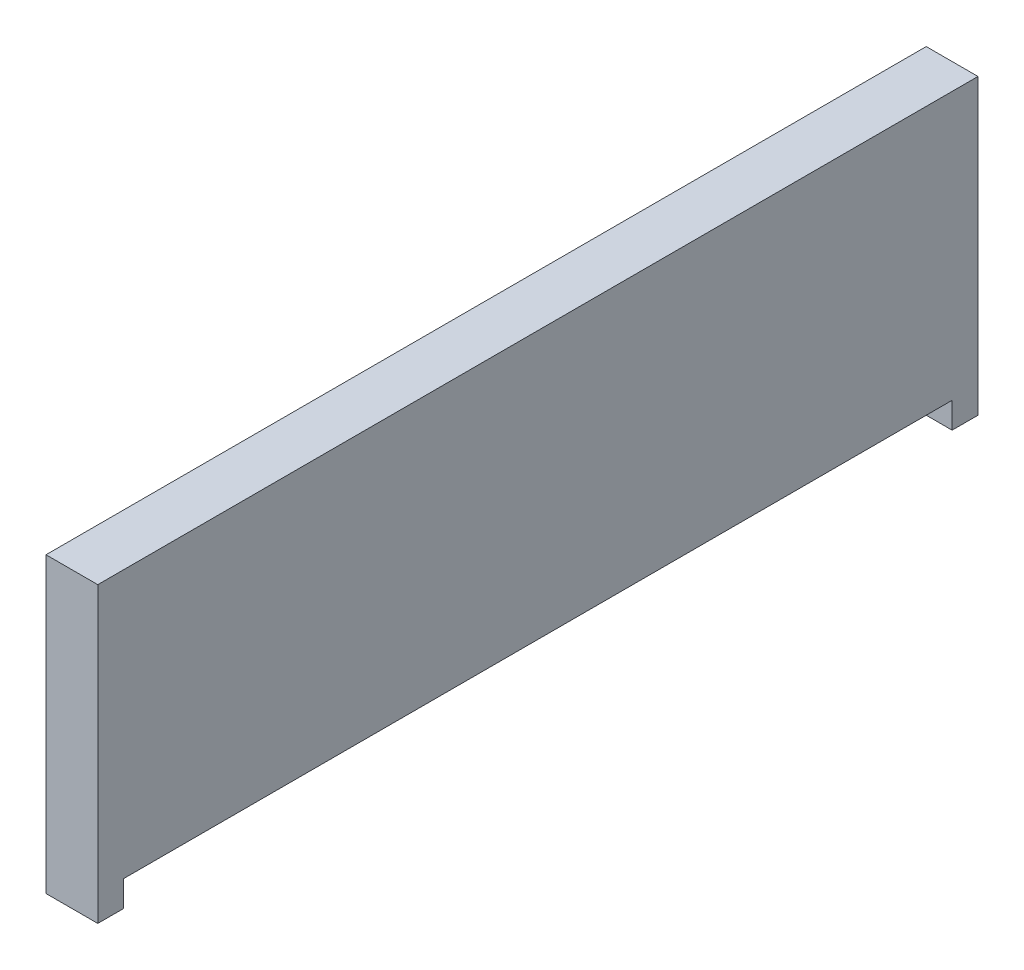
SolidWorks part; units mm, degrees
material "Сосна"
ref_plane "Спереди" through (0, 0, 0) normal (0, 0, 1) x (1, 0, 0)
ref_plane "Сверху" through (0, 0, 0) normal (0, 1, 0) x (1, 0, 0)
ref_plane "Справа" through (0, 0, 0) normal (1, 0, 0) x (0, 0, -1)
sketch "Эскиз1" plane through (0, 0, 0) normal (0, 0, 1) x (1, 0, 0)
  line L0 (0, 0) -> (15, 0)
  line L1 (15, 15) -> (30, 15)
  line L2 (15, 0) -> (15, 15)
  line L3 (30, 15) -> (30, 170)
  line L4 (30, 170) -> (0, 170)
  line L7 (0, 170) -> (0, 0)
  dimension "D1" = 155
  dimension "D2" = 30
  dimension "D3" = 15
  dimension "D4" = 15
extrude "Бобышка-Вытянуть1" add sketch "Эскиз1" along normal blind 510
sketch "Эскиз2" plane through (0, 0, 0) normal (0, 0, -1) x (-1, 0, 0)
  line L1 (-30, 15) -> (-15, 15)
  line L2 (-30, 15) -> (-30, 0)
  line L3 (-30, 0) -> (-15, 0)
  line L4 (-15, 15) -> (-15, 0)
extrude "Бобышка-Вытянуть2" add sketch "Эскиз2" against normal blind 15
pattern_linear "Линейный массив1" count 2 spacing 495 along (0, 0, 1) of "Бобышка-Вытянуть2"
